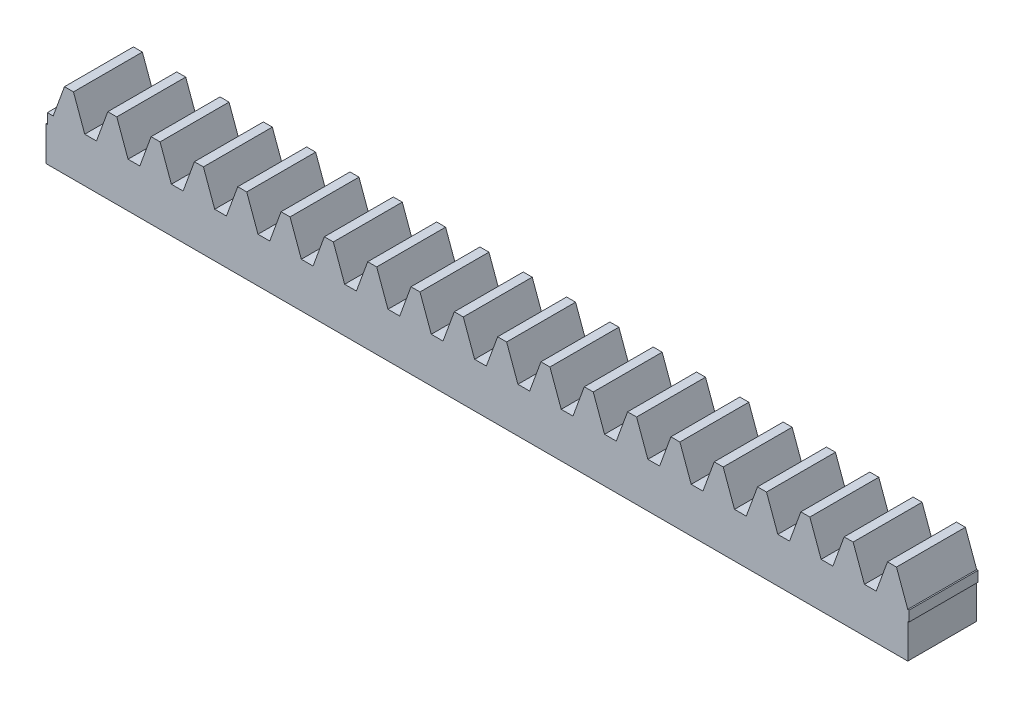
SolidWorks part; units mm, degrees
extrude "Blank" add sketch "BlankSke" against normal blind 40
sketch "BlankSke" plane through (0, 0, 0) normal (0, 0, 1) x (1, 0, 0)
  line L1 (0, 0) -> (500, 0)
  line L2 (0, 0) -> (0, 24)
  line L3 (0, 24) -> (500, 24)
  line L4 (500, 0) -> (500, 24)
  dimension "Length" = 500
  dimension "Blank_height" = 24
ref_plane "Plane1" through (0, 0, 0) normal (0, 0, 1) x (1, 0, 0)
ref_plane "Plane2" through (0, 0, 0) normal (0, 1, 0) x (1, 0, 0)
ref_plane "Plane3" through (0, 0, 0) normal (1, 0, 0) x (0, 0, -1)
sketch "HoldingSke" plane through (0, 0, 0) normal (0, 1, 0) x (1, 0, 0)
  line L0 (0, 0) -> (0.0174, 0.1238)
  line L1 (-15, 0) -> (100, 0) construction
  line L2 (0, 0) -> (-2.1039, 2.3779)
  line L3 (0, 0) -> (-11.863, 4.5341)
  line L4 (0, 0) -> (8.0624, 3.0949)
  line L5 (0, 0) -> (-23.7986, -8.8762)
  line L6 (0, 0) -> (-10.5278, -7.1032)
  line L9 (-71.009, 38.7566) -> (398.8373, 209.7667)
  line L10 (-76.2, 10.3779) -> (-60.2, 10.3779)
  line L11 (0, 0) -> (-100, 0)
  line L12 (-76.2, 101.6) -> (-75.945, 101.6)
  line L13 (24.9733, 27.94) -> (52.9518, 28.4284)
  line L14 (24.9733, 27.94) -> (24.9743, 27.94)
  line L15 (24.9733, 27.94) -> (100.4006, 29.5858)
  circle A0 centre (0, 0) radius 19.05
  circle A1 centre (0, 0) radius 8
  circle A2 centre (0, 0) radius 12.7
  dimension "MPH" = 16
  dimension "Diameter" = 38.1
  dimension "Num_teeth" = 21
  dimension "Pitch" = 0.125
  dimension "Show_teeth" = 998
  dimension "Thickness" = 12.7
  dimension "Ap" = 20
  dimension "Pitch_height" = 16
  dimension "Width" = 100
  dimension "Backlash" = 0.255
  dimension "Addendum_fac" = 1
  dimension "Dedendum_fac" = 1.25
  dimension "Clearance_fac" = 0.25
  dimension "Dedendum_add" = 0.001
  dimension "Length" = 500
  dimension "Module" = 8
sketch "TooCutSkeIll" plane through (0, 0, 0) normal (0, 0, 1) x (1, 0, 0)
  line L0 (-9.8833, 23.7894) -> (-3.8877, 7.3166)
  line L1 (-2.0074, 6) -> (2.0074, 6)
  line L2 (3.8877, 7.3166) -> (9.8833, 23.7894)
  line L3 (500, 24) -> (0, 24) construction
  line L4 (0, 0) -> (0, 64.897) construction
  line L5 (-13.208, 16) -> (12.954, 16) construction
  line L6 (0, 0) -> (500, 0) construction
  line L7 (7.0482, 16) -> (7.0482, 48.7463) construction
  line L8 (-7.0482, 16) -> (-7.0482, 48.7463) construction
  line L9 (10.184, 24) -> (10.184, 24.0254)
  line L10 (-10.184, 24) -> (-10.184, 24.0254)
  line L11 (-10.184, 24.0254) -> (10.184, 24.0254)
  arc A0 (2.0074, 6) -> (3.8877, 7.3166) centre (2.0074, 8.001) ccw
  arc A1 (-3.8877, 7.3166) -> (-2.0074, 6) centre (-2.0074, 8.001) ccw
  arc A2 (10.184, 24) -> (9.8833, 23.7894) centre (10.184, 23.68) ccw
  arc A3 (-9.8833, 23.7894) -> (-10.184, 24) centre (-10.184, 23.68) ccw
  dimension "Pitch_height" = 16
  dimension "Addendum_plus" = 8.0254
  dimension "Pressure_angle" = 20
  dimension "Gap_width" = 14.0964
  dimension "Dedendum" = 10
extrude "ToothCutIll" [suppressed] cut sketch "TooCutSkeIll" against normal through all
sketch "TooCutSkeSim" plane through (0, 0, 0) normal (0, 0, 1) x (1, 0, 0)
  line L0 (3.4085, 6) -> (-3.4085, 6)
  line L1 (9.9692, 24.0254) -> (3.4085, 6)
  line L2 (0, 17.4625) -> (0, 53.467) construction
  line L3 (9.9692, 24.0254) -> (-9.9692, 24.0254)
  line L6 (-9.9692, 24.0254) -> (-3.4085, 6)
  line L9 (-7.0482, 16) -> (7.0482, 16) construction
  line L10 (0, 0) -> (500, 0) construction
  line L11 (7.0482, 16) -> (7.0482, 53.467) construction
  line L12 (-7.0482, 16) -> (-7.0482, 53.467) construction
  dimension "Pitch_height" = 16
  dimension "Addendum_plus" = 8.0254
  dimension "Pressure_angle" = 20
  dimension "Gap_width" = 14.0964
  dimension "Dedendum" = 10
extrude "ToothCutSim" cut sketch "TooCutSkeSim" against normal through all
pattern_linear "TeethCuts" count 21 spacing 25.1327 along (1, 0, 0) of "ToothCutIll", "ToothCutSim"
sketch "Sketch1" plane through (0, 0, 0) normal (0, -1, 0) x (1, 0, 0)
  line L1 (499.2463, -40) -> (-300.7537, -40)
  line L2 (499.2463, -40) -> (499.2463, 0)
  line L3 (499.2463, 0) -> (-300.7537, 0)
  line L4 (-300.7537, -40) -> (-300.7537, 0)
  dimension "D1" = 800
extrude "Boss-Extrude1" add sketch "Sketch1" along normal blind 30
sketch "Sketch2" plane through (-300.7537, 0, 0) normal (-1, 0, 0) x (0, 0, 1)
  line L1 (-40, 0) -> (0, 0)
  line L2 (-40, 0) -> (-40, -30)
  line L3 (-40, -30) -> (0, -30)
  line L4 (0, 0) -> (0, -30)
extrude "Cut-Extrude1" cut sketch "Sketch2" against normal blind 300
sketch "Sketch3" plane through (0, -30, 0) normal (0, -1, 0) x (1, 0, 0)
  line L5 (-0.7537, 0) -> (500, 0)
  line L6 (-0.7537, 0) -> (-0.7537, -40)
  line L7 (-0.7537, -40) -> (500, -40)
  line L8 (500, 0) -> (500, -40)
extrude "Cut-Extrude3" cut sketch "Sketch3" against normal blind 10
equation "' \"Module@HoldingSke\" = 6.35"
equation "' \"Num_teeth@HoldingSke\" = 12"
equation "' \"Ap@HoldingSke\" =  20"
equation "' \"Ap@HoldingSke\" = 20"
equation "' \"Width@HoldingSke\" = 0.25 * 25.4"
equation "' \"Show_teeth@HoldingSke\" = 500"
equation "' \"Backlash@HoldingSke\" = 0.009 * 25.4"
equation "' \"Addendum_fac@HoldingSke\" = 1.0"
equation "' \"Dedendum_fac@HoldingSke\" = 1.25"
equation "' \"Dedendum_add@HoldingSke\" = 0.00005 * 25.4"
equation "' \"Clearance_fac@HoldingSke\" = 0.25"
equation "' \"Pitch_height@HoldingSke\" = 1 * 25.4"
equation "' \"Length@HoldingSke\" = 4.71 * 25.4"
equation "\"Pitch@HoldingSke\" = 1 / \"Module@HoldingSke\""
equation "\"MPH@HoldingSke\" = \"Dedendum_fac@HoldingSke\" / \"Pitch@HoldingSke\" + 2 * \"Dedendum_add@HoldingSke\" + 0.002 * 25.4"
equation "\"MPH@HoldingSke\" = ((sgn( \"MPH@HoldingSke\" - \"Pitch_height@HoldingSke\")+1)*( \"MPH@HoldingSke\" - \"Pitch_height@HoldingSke\"))/2 + \"Pitch_height@HoldingSke\""
equation "\"Blank_height@BlankSke\" = \"Pitch_height@HoldingSke\" + \"Addendum_fac@HoldingSke\"  / \"Pitch@HoldingSke\" "
equation "\"Length@BlankSke\" =  \"Length@HoldingSke\""
equation "\"Face_width@Blank\"=40"
equation "\"Pressure_angle@TooCutSkeIll\" = \"Ap@HoldingSke\""
equation "\"Addendum_plus@TooCutSkeIll\" =  \"Addendum_fac@HoldingSke\"  / \"Pitch@HoldingSke\" + 0.001 *25.4"
equation "\"Dedendum@TooCutSkeIll\" = \"Dedendum_fac@HoldingSke\"  / \"Pitch@HoldingSke\""
equation "\"Pitch_height@TooCutSkeIll\" =  \"MPH@HoldingSke\""
equation "\"Gap_width@TooCutSkeIll\" = 3.14159265 / 2 / \"Pitch@HoldingSke\" + 6 * \"Backlash@HoldingSke\""
equation "\"Pressure_angle@TooCutSkeSim\" = \"Ap@HoldingSke\""
equation "\"Addendum_plus@TooCutSkeSim\" =  \"Addendum_fac@HoldingSke\"  / \"Pitch@HoldingSke\" + 0.001 * 25.4"
equation "\"Dedendum@TooCutSkeSim\" = \"Dedendum_fac@HoldingSke\"  / \"Pitch@HoldingSke\""
equation "\"Pitch_height@TooCutSkeSim\" =  \"MPH@HoldingSke\""
equation "\"Gap_width@TooCutSkeSim\" = 3.14159265 / 2 / \"Pitch@HoldingSke\" + 6 * \"Backlash@HoldingSke\""
equation "\"Root_fillet@TooCutSkeIll\" = \"Clearance_fac@HoldingSke\" / \"Pitch@HoldingSke\" + \"Dedendum_add@HoldingSke\""
equation "\"Break_rad@TooCutSkeIll\" = 0.02 / \"Pitch@HoldingSke\" * 2"
equation "\"Linear_pitch@TeethCuts\" = 3.14159265 / \"Pitch@HoldingSke\""
equation "\"Num_teeth@HoldingSke\" = int( ( \"Length@HoldingSke\" + 0 ) / (3.14159265 / \"Pitch@HoldingSke\")) + 0.9999  + 1"
equation " \"Num_teeth@TeethCuts\" = int( \"Show_teeth@HoldingSke\" ) + 1"
equation " \"Num_teeth@TeethCuts\" = ((sgn( \"Num_teeth@TeethCuts\" - \"Num_teeth@HoldingSke\" )-1)*( \"Num_teeth@TeethCuts\" - \"Num_teeth@HoldingSke\" ))/-2+ \"Num_teeth@HoldingSke\""
equation " \"Num_teeth@TeethCuts\" = ((sgn( \"Num_teeth@TeethCuts\" - 2.0)+1)*( \"Num_teeth@TeethCuts\" - 2.0))/2 +2.0"
